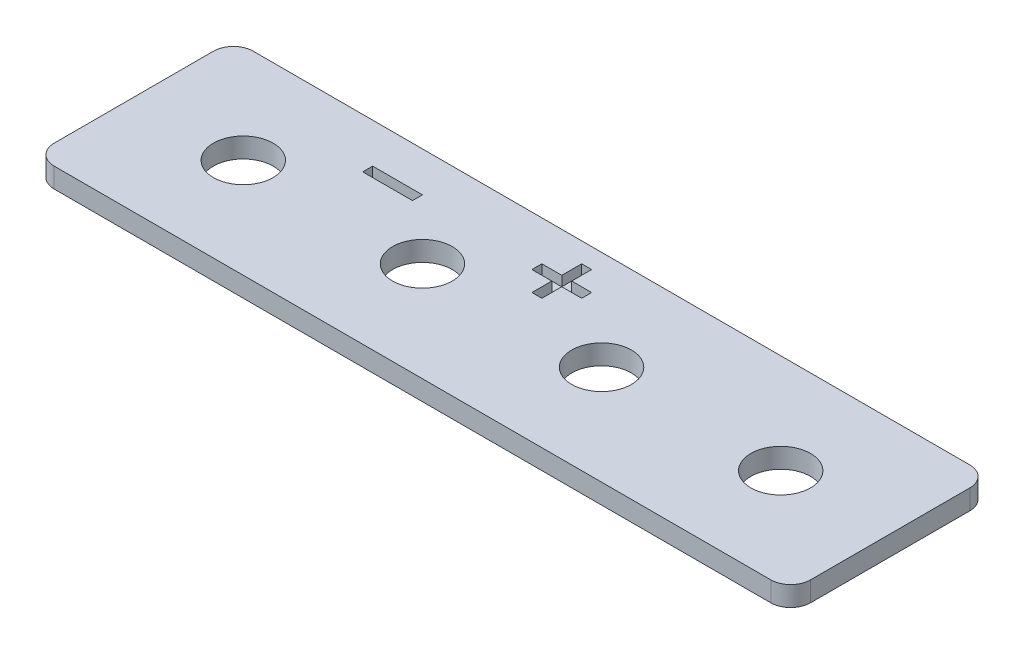
SolidWorks part; units mm, degrees
ref_plane "Спереди" through (0, 0, 0) normal (0, 0, 1) x (1, 0, 0)
ref_plane "Сверху" through (0, 0, 0) normal (0, 1, 0) x (1, 0, 0)
ref_plane "Справа" through (0, 0, 0) normal (1, 0, 0) x (0, 0, -1)
sketch "Эскиз1" plane through (0, 0, 0) normal (0, 1, 0) x (1, 0, 0)
  line L1 (-19, -5) -> (19, -5)
  line L2 (-19, -5) -> (-19, 5)
  line L3 (-19, 5) -> (19, 5)
  line L4 (19, -5) -> (19, 5)
  line L5 (-19, -5) -> (19, 5) construction
  line L6 (-19, 5) -> (19, -5) construction
  point P0 (0, 0)
  dimension "D1" = 38
  dimension "D2" = 10
extrude "Бобышка-Вытянуть1" add sketch "Эскиз1" along normal blind 1
fillet "Скругление1" radius 1 4 edges at (-19, 0.5, -5) (-19, 0.5, 5) (19, 0.5, -5) (19, 0.5, 5)
sketch "Эскиз2" plane through (0, 1, 0) normal (0, 1, 0) x (1, 0, 0)
  line L0 (-13.5, 0) -> (-4.5, 0) construction
  line L1 (-4.5, 0) -> (4.5, 0) construction
  line L2 (4.5, 0) -> (13.5, 0) construction
  circle A0 centre (-13.5, 0) radius 1.5
  circle A1 centre (-4.5, 0) radius 1.5
  circle A2 centre (4.5, 0) radius 1.5
  circle A3 centre (13.5, 0) radius 1.5
  dimension "D1" = 3
  dimension "D2" = 9
extrude "Вырез-Вытянуть1" cut sketch "Эскиз2" against normal through all
sketch "Эскиз3" plane through (0, 1, 0) normal (0, 1, 0) x (1, 0, 0)
  line L0 (0, 2.5) -> (0, 1.5)
  line L1 (-10, 3) -> (-7.5, 3)
  line L2 (-10, 3) -> (-10, 2.5)
  line L3 (-10, 2.5) -> (-7.5, 2.5)
  line L4 (-7.5, 3) -> (-7.5, 2.5)
  line L5 (-1.5, 3) -> (-0.5, 3)
  line L6 (-1.5, 3) -> (-1.5, 2.5)
  line L7 (-1.5, 2.5) -> (-0.5, 2.5)
  line L8 (1, 3) -> (1, 2.5)
  line L9 (-0.5, 4) -> (0, 4)
  line L10 (-0.5, 4) -> (-0.5, 3)
  line L11 (-0.5, 1.5) -> (0, 1.5)
  line L12 (0, 4) -> (0, 3)
  line L13 (0, 2.5) -> (1, 2.5)
  line L14 (0, 3) -> (1, 3)
  line L15 (-0.5, 2.5) -> (-0.5, 1.5)
  line L16 (-7.5, 2.5) -> (-1.5, 2.5) construction
  line L17 (-4.5, 0) -> (-4.5, 2.5) construction
  line L18 (18, 5) -> (-18, 5) construction
  dimension "D1" = 2.5
  dimension "D2" = 0.5
  dimension "D3" = 2.5
  dimension "D4" = 2
  dimension "D5" = 6
extrude "Вырез-Вытянуть2" cut sketch "Эскиз3" against normal blind 0.5
